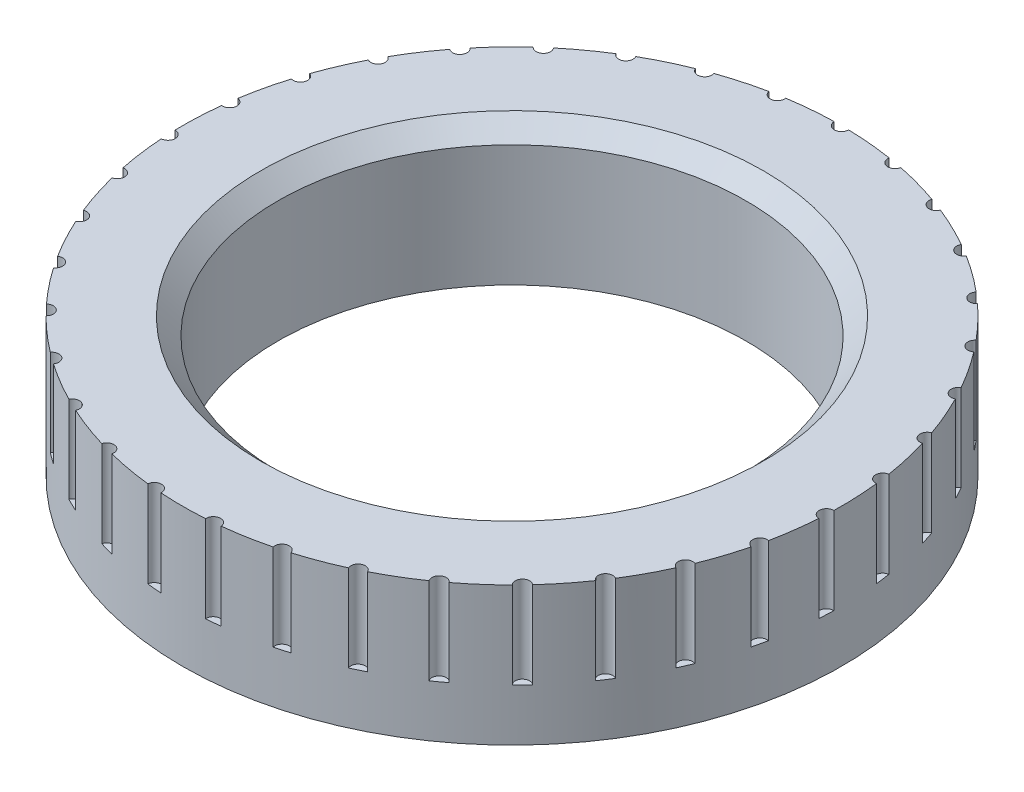
SolidWorks part; units mm, degrees
ref_plane "前视基准面" through (0, 0, 0) normal (0, 0, 1) x (1, 0, 0)
ref_plane "上视基准面" through (0, 0, 0) normal (0, 1, 0) x (1, 0, 0)
ref_plane "右视基准面" through (0, 0, 0) normal (1, 0, 0) x (0, 0, -1)
sketch "草图1" plane through (0, 0, 0) normal (0, 1, 0) x (1, 0, 0)
  circle A0 centre (0, 0) radius 19
  circle A1 centre (0, 0) radius 13.5
  dimension "D1" = 38
  dimension "D2" = 27
extrude "拉伸1" add sketch "草图1" along normal blind 8
sketch "草图2" plane through (0, 8, 0) normal (0, 1, 0) x (1, 0, 0)
  circle A0 centre (0, 19) radius 0.4153
  circle A1 centre (0, 0) radius 19 construction
  circle A2 centre (3.3926, 18.6947) radius 0.4153
  circle A3 centre (6.6761, 17.7885) radius 0.4153
  circle A4 centre (9.7451, 16.3105) radius 0.4153
  circle A5 centre (12.5008, 14.3084) radius 0.4153
  circle A6 centre (14.8548, 11.8463) radius 0.4153
  circle A7 centre (16.7313, 9.0035) radius 0.4153
  circle A8 centre (18.0701, 5.8713) radius 0.4153
  circle A9 centre (18.828, 2.5504) radius 0.4153
  circle A10 centre (18.9809, -0.8524) radius 0.4153
  circle A11 centre (18.5236, -4.2279) radius 0.4153
  circle A12 centre (17.471, -7.4675) radius 0.4153
  circle A13 centre (15.8569, -10.467) radius 0.4153
  circle A14 centre (13.7331, -13.1302) radius 0.4153
  circle A15 centre (11.1679, -15.3713) radius 0.4153
  circle A16 centre (8.2438, -17.1184) radius 0.4153
  circle A17 centre (5.0547, -18.3153) radius 0.4153
  circle A18 centre (1.7031, -18.9235) radius 0.4153
  circle A19 centre (-1.7031, -18.9235) radius 0.4153
  circle A20 centre (-5.0547, -18.3153) radius 0.4153
  circle A21 centre (-8.2438, -17.1184) radius 0.4153
  circle A22 centre (-11.1679, -15.3713) radius 0.4153
  circle A23 centre (-13.7331, -13.1302) radius 0.4153
  circle A24 centre (-15.8569, -10.467) radius 0.4153
  circle A25 centre (-17.471, -7.4675) radius 0.4153
  circle A26 centre (-18.5236, -4.2279) radius 0.4153
  circle A27 centre (-18.9809, -0.8524) radius 0.4153
  circle A28 centre (-18.828, 2.5504) radius 0.4153
  circle A29 centre (-18.0701, 5.8713) radius 0.4153
  circle A30 centre (-16.7313, 9.0035) radius 0.4153
  circle A31 centre (-14.8548, 11.8463) radius 0.4153
  circle A32 centre (-12.5008, 14.3084) radius 0.4153
  circle A33 centre (-9.7451, 16.3105) radius 0.4153
  circle A34 centre (-6.6761, 17.7885) radius 0.4153
  circle A35 centre (-3.3926, 18.6947) radius 0.4153
extrude "拉伸2" cut sketch "草图2" against normal blind 5
chamfer "倒角1" distance 1 angle 45 1 edges at (0, 8, 13.5)
